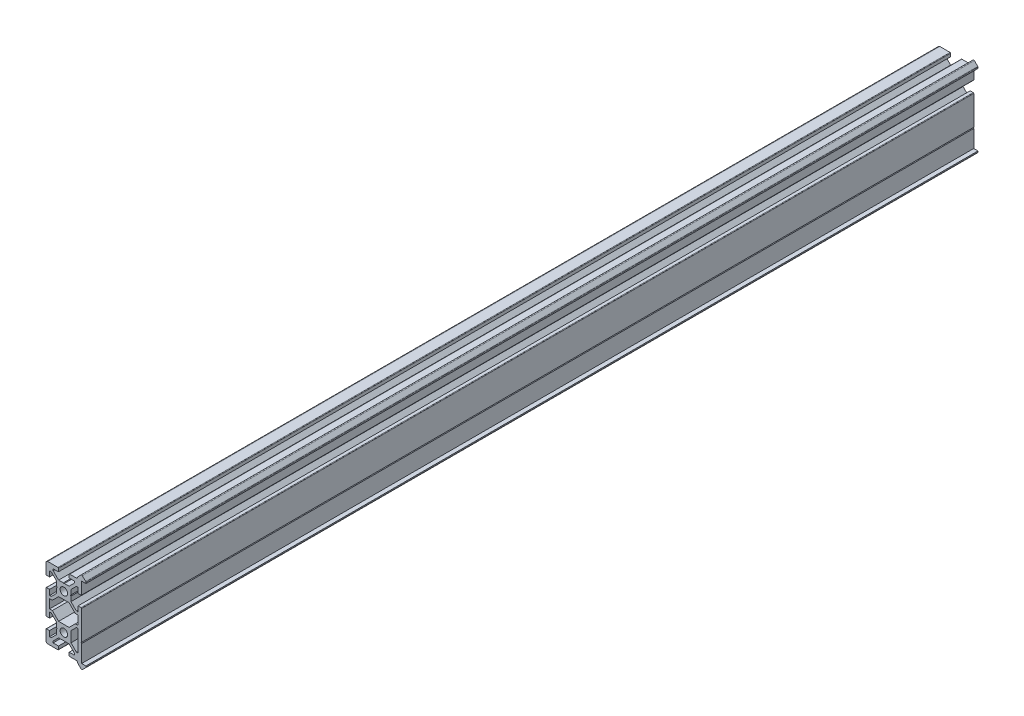
SolidWorks part; units mm, degrees
ref_plane "Front Plane" through (0, 0, 0) normal (0, 0, 1) x (1, 0, 0)
ref_plane "Top Plane" through (0, 0, 0) normal (0, 1, 0) x (1, 0, 0)
ref_plane "Right Plane" through (0, 0, 0) normal (1, 0, 0) x (0, 0, -1)
ref_plane "Plane1" through (0, 0, 0) normal (0, 0, -1) x (-1, 0, 0)
sketch "Sketch1" plane through (0, 0, 0) normal (0, 0, -1) x (-1, 0, 0)
  line L0 (-8, -4) -> (-7.0607, -4)
  line L1 (-7.0607, -4) -> (-4, -7.0607)
  line L2 (-4, -7.0607) -> (-4, -12.9393)
  line L3 (-4, -12.9393) -> (-7.0607, -16)
  line L4 (-7.0607, -16) -> (-8, -16)
  line L5 (-8, -16) -> (-8, -4)
  line L6 (8, -2.5) -> (6.4393, -2.5)
  line L7 (6.4393, -2.5) -> (2.9393, -6)
  line L8 (2.9393, -6) -> (-2.9393, -6)
  line L9 (-2.9393, -6) -> (-6.4393, -2.5)
  line L10 (-6.4393, -2.5) -> (-8, -2.5)
  line L11 (-8, -2.5) -> (-8, 2.5)
  line L12 (-8, 2.5) -> (-6.4393, 2.5)
  line L13 (-6.4393, 2.5) -> (-2.9393, 6)
  line L14 (-2.9393, 6) -> (2.9393, 6)
  line L15 (2.9393, 6) -> (6.4393, 2.5)
  line L16 (6.4393, 2.5) -> (8, 2.5)
  line L17 (8, 2.5) -> (8, -2.5)
  line L18 (-9.6464, -22.8214) -> (-7.7714, -20.9464)
  line L19 (-7.625, -20.5929) -> (-7.625, -20.5)
  line L20 (-7.125, -20) -> (-3.3, -20)
  line L21 (-3, -19.7) -> (-3, -18)
  line L22 (-3, -18) -> (-6, -18)
  line L23 (-6, -18) -> (-6, -17.0607)
  line L24 (-6, -17.0607) -> (-2.9393, -14)
  line L25 (-2.9393, -14) -> (-0.3, -14)
  line L26 (-0.3, -14) -> (0, -13.7)
  line L27 (0, -13.7) -> (0.3, -14)
  line L28 (0.3, -14) -> (2.9393, -14)
  line L29 (2.9393, -14) -> (6, -17.0607)
  line L30 (6, -17.0607) -> (6, -18)
  line L31 (6, -18) -> (3, -18)
  line L32 (3, -18) -> (3, -19.7)
  line L33 (3.3, -20) -> (9, -20)
  line L34 (10, -19) -> (10, -13.3)
  line L35 (9.7, -13) -> (8, -13)
  line L36 (8, -13) -> (8, -16)
  line L37 (8, -16) -> (7.0607, -16)
  line L38 (7.0607, -16) -> (4, -12.9393)
  line L39 (4, -12.9393) -> (4, -10.3)
  line L40 (4, -10.3) -> (3.7, -10)
  line L41 (3.7, -10) -> (4, -9.7)
  line L42 (4, -9.7) -> (4, -7.0607)
  line L43 (4, -7.0607) -> (7.0607, -4)
  line L44 (7.0607, -4) -> (8, -4)
  line L45 (8, -4) -> (8, -7)
  line L46 (8, -7) -> (9.7, -7)
  line L47 (10, -6.7) -> (10, 6.7)
  line L48 (9.7, 7) -> (8, 7)
  line L49 (8, 7) -> (8, 4)
  line L50 (8, 4) -> (7.0607, 4)
  line L51 (7.0607, 4) -> (4, 7.0607)
  line L52 (4, 7.0607) -> (4, 9.7)
  line L53 (4, 9.7) -> (3.7, 10)
  line L54 (3.7, 10) -> (4, 10.3)
  line L55 (4, 10.3) -> (4, 12.9393)
  line L56 (4, 12.9393) -> (7.0607, 16)
  line L57 (7.0607, 16) -> (8, 16)
  line L58 (8, 16) -> (8, 13)
  line L59 (8, 13) -> (9.7, 13)
  line L60 (10, 13.3) -> (10, 19)
  line L61 (9, 20) -> (3.3, 20)
  line L62 (3, 19.7) -> (3, 18)
  line L63 (3, 18) -> (6, 18)
  line L64 (6, 18) -> (6, 17.0607)
  line L65 (6, 17.0607) -> (2.9393, 14)
  line L66 (2.9393, 14) -> (0.3, 14)
  line L67 (0.3, 14) -> (0, 13.7)
  line L68 (0, 13.7) -> (-0.3, 14)
  line L69 (-0.3, 14) -> (-2.9393, 14)
  line L70 (-2.9393, 14) -> (-6, 17.0607)
  line L71 (-6, 17.0607) -> (-6, 18)
  line L72 (-6, 18) -> (-3, 18)
  line L73 (-3, 18) -> (-3, 19.7)
  line L74 (-3.3, 20) -> (-7.125, 20)
  line L75 (-7.625, 20.5) -> (-7.625, 20.5929)
  line L76 (-7.7714, 20.9464) -> (-9.6464, 22.8214)
  line L77 (-10.3536, 22.8214) -> (-12.2286, 20.9464)
  line L78 (-12.375, 20.5929) -> (-12.375, 20)
  line L79 (-12.375, 20) -> (-10, 20)
  line L80 (-10, 20) -> (-10, 13.3)
  line L81 (-9.7, 13) -> (-8, 13)
  line L82 (-8, 13) -> (-8, 16)
  line L83 (-8, 16) -> (-7.0607, 16)
  line L84 (-7.0607, 16) -> (-4, 12.9393)
  line L85 (-4, 12.9393) -> (-4, 10.3)
  line L86 (-4, 10.3) -> (-3.7, 10)
  line L87 (-3.7, 10) -> (-4, 9.7)
  line L88 (-4, 9.7) -> (-4, 7.0607)
  line L89 (-4, 7.0607) -> (-7.0607, 4)
  line L90 (-7.0607, 4) -> (-8, 4)
  line L91 (-8, 4) -> (-8, 7)
  line L92 (-8, 7) -> (-9.7, 7)
  line L93 (-10, 6.7) -> (-10, -9.7)
  line L94 (-10, -9.7) -> (-9.7, -10)
  line L95 (-9.7, -10) -> (-10, -10.3)
  line L96 (-10, -10.3) -> (-10, -20)
  line L97 (-10, -20) -> (-12.375, -20)
  line L98 (-12.375, -20) -> (-12.375, -20.5929)
  line L99 (-12.2286, -20.9464) -> (-10.3536, -22.8214)
  circle A0 centre (0, 10) radius 2.1
  circle A1 centre (0, -10) radius 2.1
  arc A2 (-10.3536, -22.8214) -> (-9.6464, -22.8214) centre (-10, -22.4679) ccw
  arc A3 (-7.7714, -20.9464) -> (-7.625, -20.5929) centre (-8.125, -20.5929) ccw
  arc A4 (-7.625, -20.5) -> (-7.125, -20) centre (-7.125, -20.5) cw
  arc A5 (-3.3, -20) -> (-3, -19.7) centre (-3.3, -19.7) ccw
  arc A6 (3, -19.7) -> (3.3, -20) centre (3.3, -19.7) ccw
  arc A7 (9, -20) -> (10, -19) centre (9, -19) ccw
  arc A8 (10, -13.3) -> (9.7, -13) centre (9.7, -13.3) ccw
  arc A9 (9.7, -7) -> (10, -6.7) centre (9.7, -6.7) ccw
  arc A10 (10, 6.7) -> (9.7, 7) centre (9.7, 6.7) ccw
  arc A11 (9.7, 13) -> (10, 13.3) centre (9.7, 13.3) ccw
  arc A12 (10, 19) -> (9, 20) centre (9, 19) ccw
  arc A13 (3.3, 20) -> (3, 19.7) centre (3.3, 19.7) ccw
  arc A14 (-3, 19.7) -> (-3.3, 20) centre (-3.3, 19.7) ccw
  arc A15 (-7.125, 20) -> (-7.625, 20.5) centre (-7.125, 20.5) cw
  arc A16 (-7.625, 20.5929) -> (-7.7714, 20.9464) centre (-8.125, 20.5929) ccw
  arc A17 (-9.6464, 22.8214) -> (-10.3536, 22.8214) centre (-10, 22.4679) ccw
  arc A18 (-12.2286, 20.9464) -> (-12.375, 20.5929) centre (-11.875, 20.5929) ccw
  arc A19 (-10, 13.3) -> (-9.7, 13) centre (-9.7, 13.3) ccw
  arc A20 (-9.7, 7) -> (-10, 6.7) centre (-9.7, 6.7) ccw
  arc A21 (-12.375, -20.5929) -> (-12.2286, -20.9464) centre (-11.875, -20.5929) ccw
extrude "Boss-Extrude1" add sketch "Sketch1" against normal blind 500
